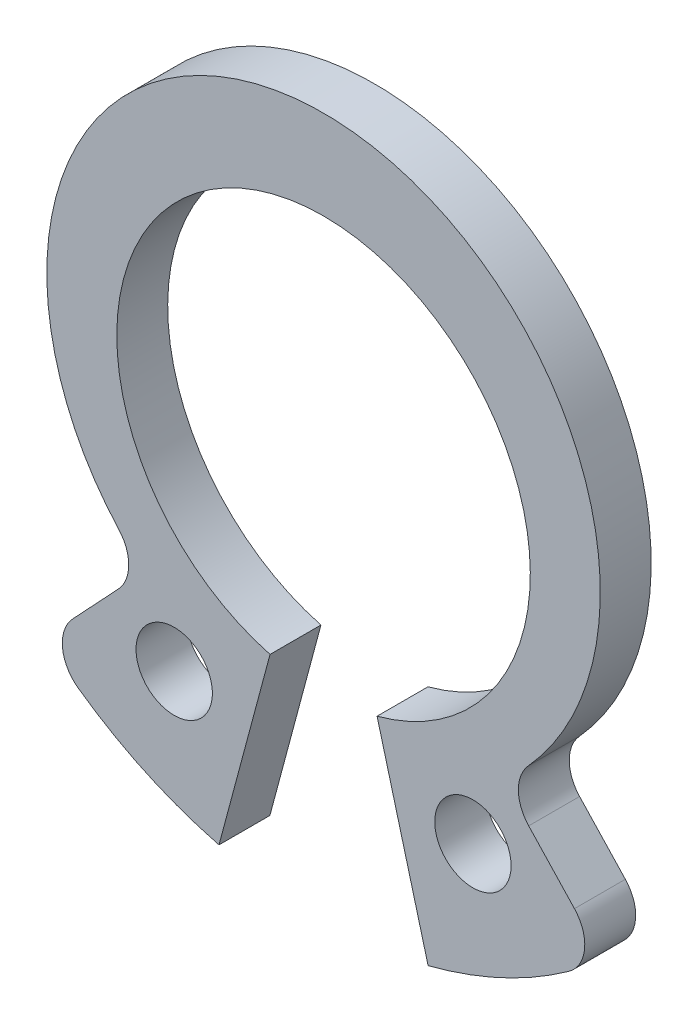
SolidWorks part; units mm, degrees
ref_plane "Plan1" through (0, 0, 0) normal (0, 0, 1) x (1, 0, 0)
ref_plane "Plan2" through (0, 0, 0) normal (0, 1, 0) x (1, 0, 0)
ref_plane "Plan3" through (0, 0, 0) normal (1, 0, 0) x (0, 0, -1)
sketch "Esquisse1" plane through (0, 0, 0) normal (0, 0, 1) x (1, 0, 0)
  line L0 (0, 0) -> (1.6435, -6.1336) construction
  line L1 (0, 0) -> (0, -67.082) construction
  line L2 (3.2245, -3.4405) -> (3.944, -4.2081)
  line L3 (0.8412, -3.1393) -> (1.6435, -6.1336)
  line L4 (-0.8412, -3.1393) -> (-1.6435, -6.1336)
  line L5 (-3.2245, -3.4405) -> (-3.944, -4.2081)
  line L6 (0.8412, -3.1393) -> (3.8545, -5.107) construction
  line L7 (0, 0) -> (0, 3.25) construction
  line L8 (0, 3.25) -> (0, 4.65) construction
  arc A0 (0.8412, -3.1393) -> (-0.8412, -3.1393) centre (0, 0) ccw
  arc A1 (1.6435, -6.1336) -> (3.8545, -5.107) centre (0, 0.3) ccw
  arc A2 (3.2184, -2.6265) -> (-3.2184, -2.6265) centre (0, 0.3) ccw
  arc A3 (-3.8545, -5.107) -> (-1.6435, -6.1336) centre (0, 0.3) ccw
  arc A4 (-3.2184, -2.6265) -> (-3.2245, -3.4405) centre (-3.6623, -3.0302) cw
  arc A5 (3.2184, -2.6265) -> (3.2245, -3.4405) centre (3.6623, -3.0302) ccw
  circle A6 centre (2.3478, -4.1231) radius 0.6
  circle A7 centre (-2.3478, -4.1231) radius 0.6
  arc A8 (-3.8545, -5.107) -> (-3.944, -4.2081) centre (-3.5062, -4.6184) cw
  arc A9 (3.8545, -5.107) -> (3.944, -4.2081) centre (3.5062, -4.6184) ccw
  point P22 (-4.389, -4.6829)
  dimension "D1" = 6.5
  dimension "D2" = 3.1
  dimension "D3" = 1.4
  dimension "R" = 0.6
  dimension "D8" = 1.2
  dimension "D4" = 0.3
  dimension "D5" = 3
  dimension "a" = 15
extrude "Base-Extrusion" add sketch "Esquisse1" along normal blind 0.8
equation "\"R@Esquisse1\" = \"D8@Esquisse1\"/2"
equation "\"D4@Esquisse1\"=\"R@Esquisse1\"/2"
equation "\"D5@Esquisse1\"=\"D8@Esquisse1\"*2.5"
